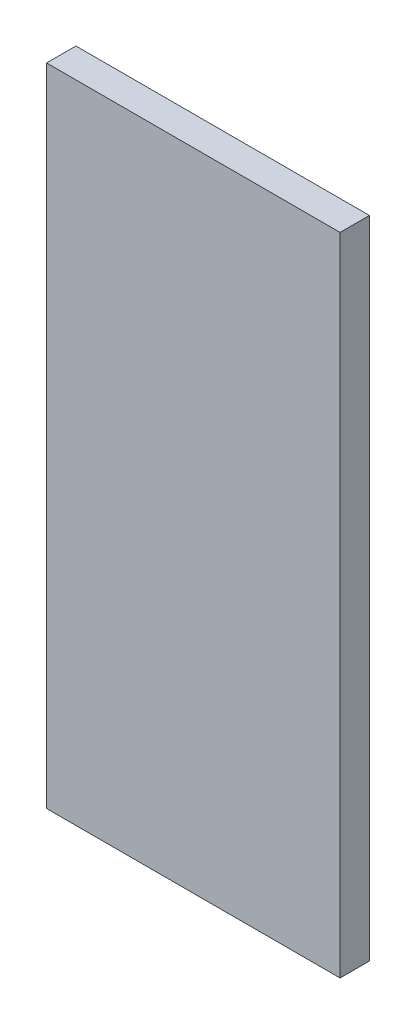
SolidWorks part; units mm, degrees
ref_plane "Front Plane" through (0, 0, 0) normal (0, 0, 1) x (1, 0, 0)
ref_plane "Top Plane" through (0, 0, 0) normal (0, 1, 0) x (1, 0, 0)
ref_plane "Right Plane" through (0, 0, 0) normal (1, 0, 0) x (0, 0, -1)
sketch "Sketch1" plane through (0, 0, 0) normal (0, 0, 1) x (1, 0, 0)
  line L1 (0, 0) -> (127, 0)
  line L2 (0, 0) -> (0, 279.4)
  line L3 (0, 279.4) -> (127, 279.4)
  line L4 (127, 0) -> (127, 279.4)
  dimension "D1" = 279.4
  dimension "D2" = 127
extrude "Boss-Extrude1" add sketch "Sketch1" along normal blind 12.7
